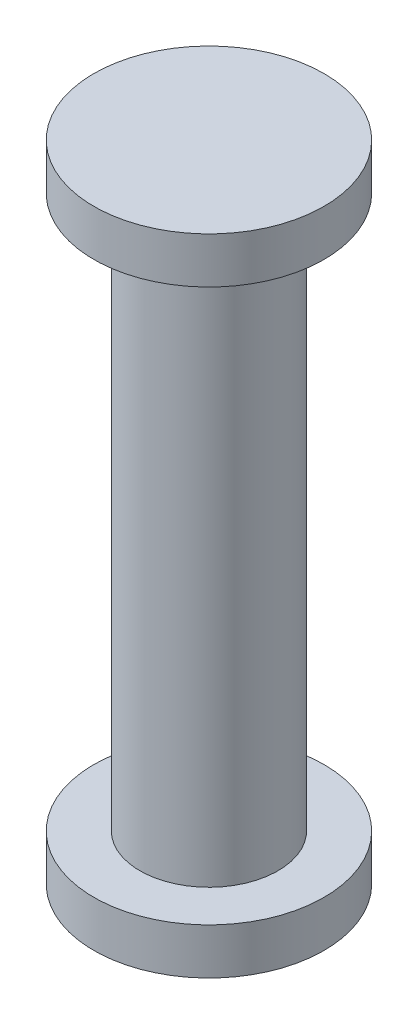
SolidWorks part; units mm, degrees
ref_plane "Front Plane" through (0, 0, 0) normal (0, 0, 1) x (1, 0, 0)
ref_plane "Top Plane" through (0, 0, 0) normal (0, 1, 0) x (1, 0, 0)
ref_plane "Right Plane" through (0, 0, 0) normal (1, 0, 0) x (0, 0, -1)
sketch "Sketch1" plane through (0, 0, 0) normal (0, 0, 1) x (1, 0, 0)
  line L0 (0, 0) -> (0, 14)
  line L1 (0, 14) -> (-2.5, 14)
  line L3 (-1.5, 1) -> (-2.5, 1)
  line L4 (-2.5, 1) -> (-2.5, 0)
  line L5 (-2.5, 0) -> (0, 0)
  line L6 (-2.5, 14) -> (-2.5, 13)
  line L7 (-2.5, 13) -> (-1.5, 13)
  line L8 (-1.5, 13) -> (-1.5, 1)
  dimension "D1" = 1
  dimension "D2" = 2.5
  dimension "D3" = 14
  dimension "D4" = 1.5
  dimension "D5" = 1
revolve "Revolve1" add sketch "Sketch1" angle 360 about L0
